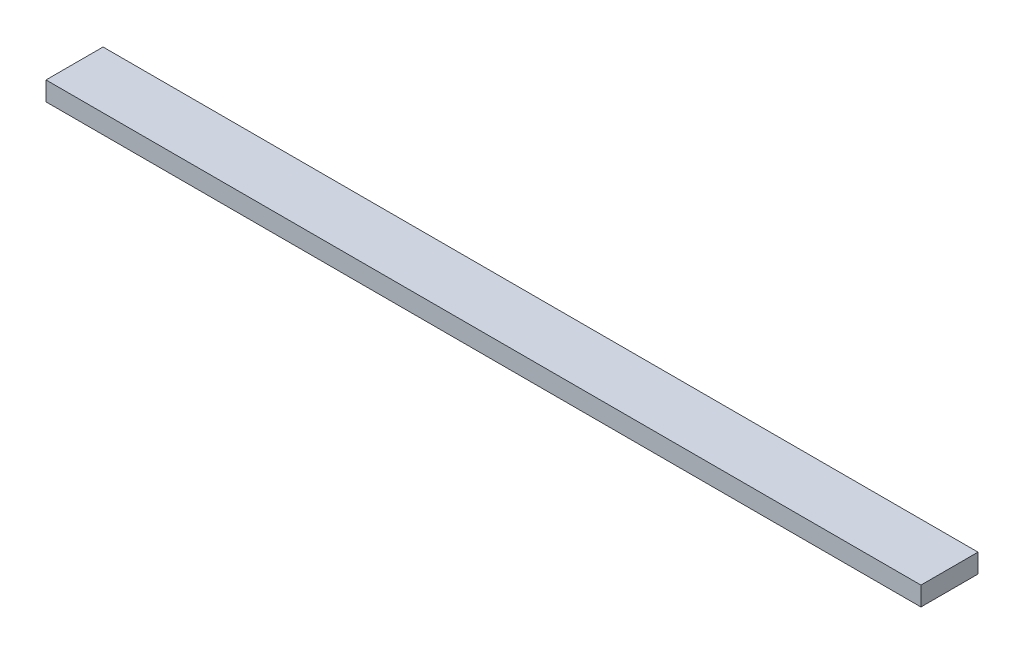
SolidWorks part; units mm, degrees
material "Pine"
ref_plane "Front Plane" through (0, 0, 0) normal (0, 0, 1) x (1, 0, 0)
ref_plane "Top Plane" through (0, 0, 0) normal (0, 1, 0) x (1, 0, 0)
ref_plane "Right Plane" through (0, 0, 0) normal (1, 0, 0) x (0, 0, -1)
sketch "Sketch1" plane through (0, 0, 0) normal (0, 1, 0) x (1, 0, 0)
  line L1 (0, 0) -> (2300, 0)
  line L2 (0, 0) -> (0, 150)
  line L3 (0, 150) -> (2300, 150)
  line L4 (2300, 0) -> (2300, 150)
  dimension "D1" = 150
  dimension "D2" = 2300
extrude "Boss-Extrude1" add sketch "Sketch1" along normal blind 50
